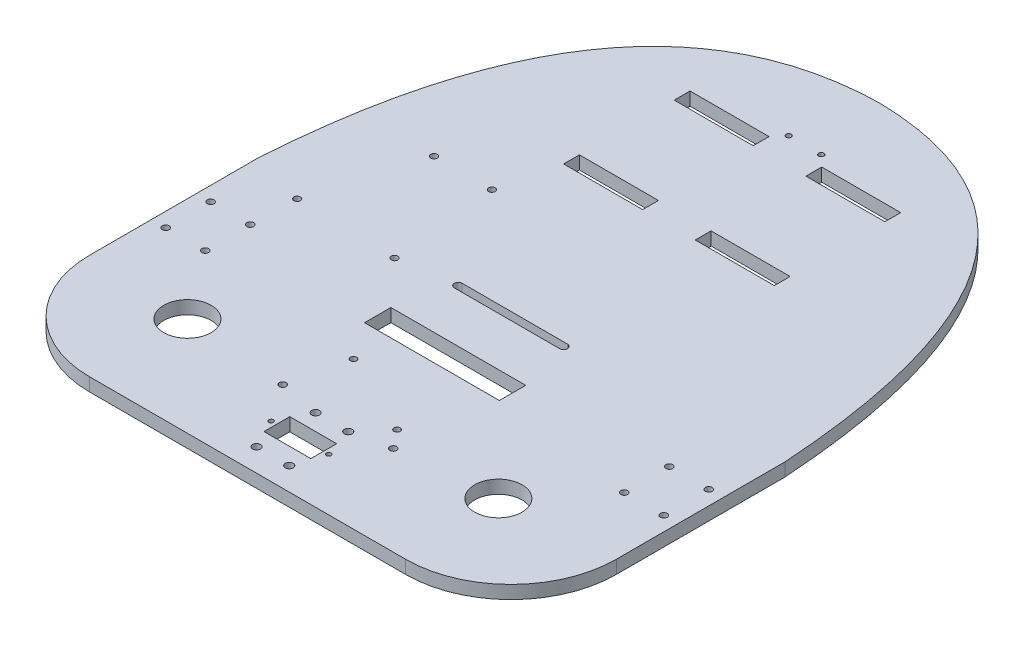
SolidWorks part; units mm, degrees
ref_plane "Front Plane" through (0, 0, 0) normal (0, 0, 1) x (1, 0, 0)
ref_plane "Top Plane" through (0, 0, 0) normal (0, 1, 0) x (1, 0, 0)
ref_plane "Right Plane" through (0, 0, 0) normal (1, 0, 0) x (0, 0, -1)
sketch "Sketch1" plane through (0, 0, 0) normal (0, 1, 0) x (1, 0, 0)
  line L0 (-50.8, 0) -> (-203.2, 0)
  line L1 (-254, 50.8) -> (-254, 132.0975)
  line L2 (0, 50.8) -> (0, 132.0975)
  arc A0 (-50.8, 0) -> (0, 50.8) centre (-50.8, 50.8) ccw
  arc A1 (-203.2, 0) -> (-254, 50.8) centre (-203.2, 50.8) cw
  spline S0 degree 2 poles (-254, 50.8) (-267.8873, 307.0061) (-122.067, 304.8) knots 0 0 0 1 1 1
  spline S1 degree 2 poles (0, 50.8) (13.8873, 307.0061) (-131.933, 304.8) knots 0 0 0 1 1 1
  point P7 (0, 0)
  dimension "D1" = 81.2975
extrude "Boss-Extrude1" add sketch "Sketch1" along normal blind 6.35 contours L2 S1 S0 L1 A1 L0 A0
sketch "Sketch2" plane through (0, 6.35, 0) normal (0, 1, 0) x (1, 0, 0)
  line L0 (-50.8, 0) -> (-203.2, 0) construction
  circle A0 centre (-119.126, 269.24) radius 1.27
  circle A1 centre (-135.3438, 269.24) radius 1.27
  dimension "D1" = 2.54
  dimension "D2" = 2.54
  dimension "D3" = 16.2178
  dimension "D4" = 269.24
extrude "Cut-Extrude1" cut sketch "Sketch2" against normal through all contours A1
sketch "Sketch5" plane through (0, 6.35, 0) normal (0, 1, 0) x (1, 0, 0)
  line L0 (-135.3438, 269.24) -> (-119.5958, 269.24)
  circle A0 centre (-119.5958, 269.24) radius 1.27
  dimension "D1" = 2.54
extrude "Cut-Extrude2" cut sketch "Sketch5" against normal through all contours A0
sketch "Sketch6" plane through (0, 6.35, 0) normal (0, 1, 0) x (1, 0, 0)
  line L0 (-50.8, 0) -> (-203.2, 0) construction
  line L1 (-177.8, 210.82) -> (-139.7, 210.82)
  line L2 (-177.8, 256.54) -> (-139.7, 256.54)
  line L5 (-177.8, 210.82) -> (-177.8, 203.2)
  line L6 (-177.8, 203.2) -> (-139.7, 203.2)
  line L7 (-139.7, 203.2) -> (-139.7, 210.82)
  line L10 (-139.7, 264.16) -> (-139.7, 256.54)
  line L11 (-177.8, 264.16) -> (-139.7, 264.16)
  line L12 (-177.8, 256.54) -> (-177.8, 264.16)
  line L25 (-254, 50.8) -> (-254, 132.0975) construction
  line L26 (-127, 304.8) -> (-127, 0) construction
  line L27 (-76.2, 210.82) -> (-76.2, 203.2)
  line L28 (-76.2, 203.2) -> (-114.3, 203.2)
  line L29 (-114.3, 203.2) -> (-114.3, 210.82)
  line L30 (-76.2, 210.82) -> (-114.3, 210.82)
  line L31 (-76.2, 256.54) -> (-76.2, 264.16)
  line L32 (-76.2, 256.54) -> (-114.3, 256.54)
  line L33 (-114.3, 264.16) -> (-114.3, 256.54)
  line L34 (-76.2, 264.16) -> (-114.3, 264.16)
  dimension "D4" = 76.2
  dimension "D5" = 203.2
  dimension "D6" = 76.2
  dimension "D7" = 38.1
  dimension "D8" = 7.62
extrude "Cut-Extrude5" cut sketch "Sketch6" against normal through all
sketch "Sketch12" plane through (0, 6.35, 0) normal (0, 1, 0) x (1, 0, 0)
  line L0 (-127, 48.6691) -> (-127, 50048.6691) construction
  line L1 (-127, 0) -> (-127, 48.6691) construction
  line L2 (-50.8, 0) -> (-203.2, 0) construction
  line L3 (-152.4, 125.095) -> (-101.6, 125.095)
  line L4 (-159.512, 101.6) -> (-159.512, 88.9)
  line L5 (-159.512, 88.9) -> (-145.2036, 88.9)
  line L6 (-145.2036, 88.9) -> (-94.5, 88.9)
  line L7 (-94.5, 101.6) -> (-94.5, 88.9)
  line L8 (-159.512, 101.6) -> (-94.5, 101.6)
  line L9 (-152.4, 128.905) -> (-101.6, 128.905)
  arc A0 (-152.4, 128.905) -> (-152.4, 125.095) centre (-152.4, 127) ccw
  arc A1 (-101.6, 128.905) -> (-101.6, 125.095) centre (-101.6, 127) cw
  dimension "D1" = 3.81
  dimension "D3" = 25.4
  dimension "D2" = 127
  dimension "D5" = 25.4
  dimension "D6" = 65.012
  dimension "D7" = 12.7
  dimension "D8" = 7.112
extrude "Cut-Extrude9" cut sketch "Sketch12" against normal through all
sketch "Sketch15" plane through (0, 6.35, 0) normal (0, 1, 0) x (1, 0, 0)
  line L0 (-127, 0) -> (-127, 304.8) construction
  line L1 (-50.8, 0) -> (-203.2, 0) construction
  line L3 (-138.303, 19.177) -> (-115.697, 19.177)
  line L4 (-138.303, 19.177) -> (-138.303, 31.623)
  line L5 (-138.303, 31.623) -> (-115.697, 31.623)
  line L6 (-115.697, 19.177) -> (-115.697, 31.623)
  line L7 (-138.303, 19.177) -> (-115.697, 31.623) construction
  line L8 (-138.303, 31.623) -> (-115.697, 19.177) construction
  point P5 (-127, 25.4)
  dimension "D1" = 22.606
  dimension "D2" = 12.446
  dimension "D3" = 25.4
extrude "Cut-Extrude12" cut sketch "Sketch15" against normal through all
extrude "Cut-Extrude13" cut sketch "Sketch17" against normal through all
sketch "Sketch17" plane through (-70.8976, -2.5, -15.5843) normal (0, -1, 0) x (1, 0, 0)
  line L1 (-70.0554, -10.7927) -> (-70.0554, -8.5927) construction
  line L2 (-68.9554, -9.6927) -> (-72.2786, -9.6927) construction
  line L3 (-56.1554, -15.7927) -> (-56.1554, 11.8367) construction
  circle A1 centre (-70.0554, -9.6927) radius 1.1
  circle A2 centre (-42.2554, -9.6927) radius 1.1
  point P8 (-70.0554, -9.6927)
  point P13 (-70.0554, -9.6927)
extrude "Cut-Extrude14" cut sketch "Sketch18" along normal through all
sketch "Sketch18" plane through (-70.8976, 6.35, -15.5843) normal (0, -1, 0) x (1, 0, 0)
  circle A0 centre (-108.3662, -107.5373) radius 1.5875
  circle A1 centre (-156.6262, -108.8073) radius 1.5875
  circle A2 centre (-141.3862, -159.6073) radius 1.5875
  circle A3 centre (-113.4462, -159.6073) radius 1.5875
  circle A5 centre (-36.1374, -36.5063) radius 1.5
  circle A6 centre (-76.1374, -55.5063) radius 1.5
  circle A7 centre (-82.4685, -27.7307) radius 1.651
  circle A8 centre (-29.1285, -27.7307) radius 1.651
extrude "Cut-Extrude15" cut sketch "Sketch19" against normal through all
sketch "Sketch19" plane through (-70.8976, 0, -15.5843) normal (0, -1, 0) x (1, 0, 0)
  circle A0 centre (-176.2124, -65.0145) radius 1.65
  circle A1 centre (-157.1624, -65.0145) radius 1.65
  circle A2 centre (-176.2124, -86.7145) radius 1.65
  circle A3 centre (-157.1624, -86.7145) radius 1.65
  circle A5 centre (64.0076, -86.7145) radius 1.65
  circle A6 centre (44.9576, -86.7145) radius 1.65
  circle A7 centre (44.9576, -65.0145) radius 1.65
  circle A8 centre (64.0076, -65.0145) radius 1.65
sketch "Sketch20" plane through (0, 6.35, 0) normal (0, 1, 0) x (1, 0, 0)
  circle A0 centre (-53.8262, 47.7576) radius 11.43
  circle A1 centre (-203.7794, 47.7576) radius 11.43
  dimension "D1" = 22.86
  dimension "D2" = 22.86
extrude "Cut-Extrude16" cut sketch "Sketch20" against normal through all
extrude "Cut-Extrude20" cut sketch "Sketch24" against normal through all
sketch "Sketch24" plane through (-70.8976, 0, -15.5843) normal (0, -1, 0) x (1, 0, 0)
  circle A0 centre (-62.8294, -23.9167) radius 1.905
  circle A1 centre (-47.0814, -23.9167) radius 1.905
  circle A2 centre (-47.0814, 4.5313) radius 1.905
  circle A3 centre (-62.8294, 4.5313) radius 1.905
